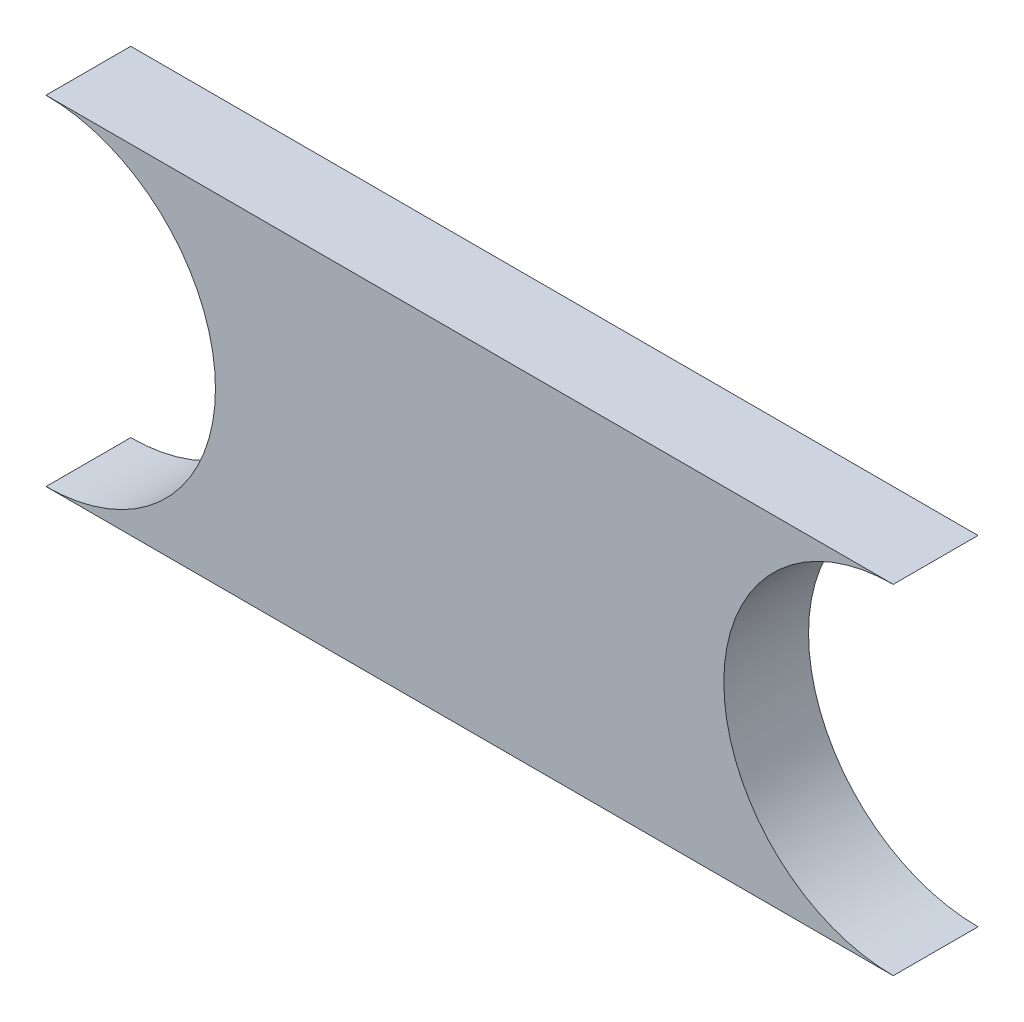
SolidWorks part; units mm, degrees
ref_plane "Front Plane" through (0, 0, 0) normal (0, 0, 1) x (1, 0, 0)
ref_plane "Top Plane" through (0, 0, 0) normal (0, 1, 0) x (1, 0, 0)
ref_plane "Right Plane" through (0, 0, 0) normal (1, 0, 0) x (0, 0, -1)
sketch "Sketch4" plane through (0, 0, 0) normal (0, 0, 1) x (1, 0, 0)
  line L0 (-13.7836, 25.4) -> (113.2164, 25.4)
  line L2 (113.2164, -25.4) -> (-13.7836, -25.4)
  arc A1 (-13.7836, 25.4) -> (-13.7836, -25.4) centre (-13.7836, 0) cw
  arc A2 (113.2164, 25.4) -> (113.2164, -25.4) centre (113.2164, 0) ccw
  dimension "D1" = 50.8
  dimension "D2" = 127
extrude "Boss-Extrude2" add sketch "Sketch4" along normal blind 12.7
